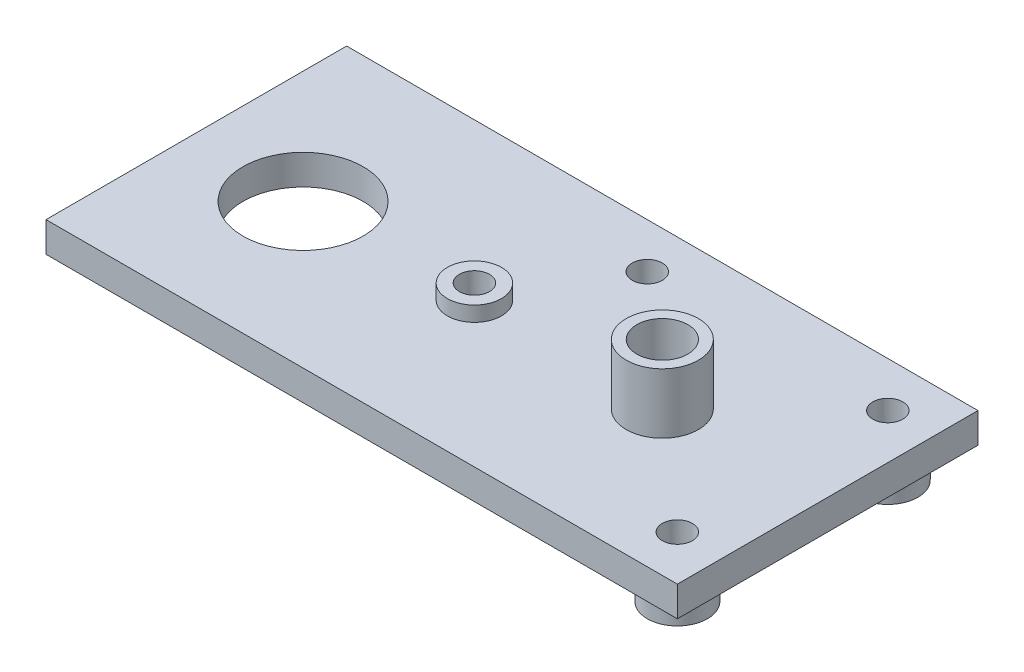
SolidWorks part; units mm, degrees
ref_plane "前视基准面" through (0, 0, 0) normal (0, 0, 1) x (1, 0, 0)
ref_plane "上视基准面" through (0, 0, 0) normal (0, 1, 0) x (1, 0, 0)
ref_plane "右视基准面" through (0, 0, 0) normal (1, 0, 0) x (0, 0, -1)
sketch "草图1" plane through (0, 0, 0) normal (0, 1, 0) x (1, 0, 0)
  line L1 (-10.5, 5) -> (10.5, 5)
  line L2 (-10.5, 5) -> (-10.5, -5)
  line L3 (-10.5, -5) -> (10.5, -5)
  line L4 (10.5, 5) -> (10.5, -5)
  line L5 (-10.5, 5) -> (10.5, -5) construction
  line L6 (-10.5, -5) -> (10.5, 5) construction
  point P0 (0, 0)
  dimension "D1" = 21
  dimension "D2" = 10
extrude "凸台-拉伸1" add sketch "草图1" along normal blind 1
sketch "草图2" plane through (0, 1, 0) normal (0, 1, 0) x (1, 0, 0)
  line L0 (-10.5, -5) -> (10.5, -5) construction
  line L1 (10.5, -5) -> (10.5, 5) construction
  circle A0 centre (5.2, -0.2) radius 1.2
  dimension "D1" = 2.4
  dimension "D2" = 4.8
  dimension "D3" = 5.3
extrude "凸台-拉伸2" add sketch "草图2" along normal blind 2
sketch "草图3" plane through (0, 3, 0) normal (0, 1, 0) x (1, 0, 0)
  circle A0 centre (5.2, -0.2) radius 0.85
  dimension "D1" = 1.7
extrude "切除-拉伸2" cut sketch "草图3" against normal blind 3
sketch "草图5" plane through (0, 1, 0) normal (0, 1, 0) x (1, 0, 0)
  line L0 (-10.5, -5) -> (10.5, -5) construction
  circle A0 centre (-1.05, -0.2) radius 0.9
  circle A1 centre (5.2, -0.2) radius 1.2 construction
  dimension "D2" = 1.8
  dimension "D1" = 4.8
  dimension "D3" = 6.25
extrude "凸台-拉伸3" add sketch "草图5" along normal blind 0.5 and the other way blind 2
sketch "草图7" plane through (0, 1, 0) normal (0, 1, 0) x (1, 0, 0)
  line L0 (-10.5, -5) -> (10.5, -5) construction
  circle A0 centre (-6.75, -0.2) radius 2
  circle A1 centre (-1.05, -0.2) radius 0.9 construction
  dimension "D2" = 4
  dimension "D1" = 5.7
  dimension "D3" = 4.8
extrude "切除-拉伸4" cut sketch "草图7" against normal blind 1
sketch "草图8" plane through (0, 1, 0) normal (0, 1, 0) x (1, 0, 0)
  line L0 (10.5, 5) -> (-10.5, 5) construction
  line L1 (10.5, -5) -> (10.5, 5) construction
  line L2 (-10.5, -5) -> (10.5, -5) construction
  circle A0 centre (9, 3.5) radius 0.5
  circle A1 centre (1, 3.5) radius 0.5
  circle A2 centre (9, -3.5) radius 0.5
  dimension "D1" = 1
  dimension "D2" = 1
  dimension "D3" = 1
  dimension "D4" = 1.5
  dimension "D8" = 1.5
  dimension "D5" = 1.5
  dimension "D6" = 1.5
  dimension "D7" = 8
  dimension "D9" = 1.5
extrude "切除-拉伸5" cut sketch "草图8" against normal blind 1
sketch "草图9" plane through (0, 1.5, 0) normal (0, 1, 0) x (1, 0, 0)
  circle A0 centre (-1.05, -0.2) radius 0.5
  dimension "D1" = 1
extrude "切除-拉伸6" cut sketch "草图9" against normal blind 2
sketch "草图10" plane through (0, 0, 0) normal (0, -1, 0) x (1, 0, 0)
  circle A0 centre (9, 3.5) radius 1
  circle A1 centre (9, -3.5) radius 1
  circle A2 centre (1, -3.5) radius 1
  dimension "D1" = 2
  dimension "D2" = 2
  dimension "D3" = 2
extrude "凸台-拉伸4" add sketch "草图10" along normal blind 1
sketch "草图11" plane through (0, -1, 0) normal (0, -1, 0) x (1, 0, 0)
  circle A0 centre (9, 3.5) radius 0.5
  circle A1 centre (9, -3.5) radius 0.5
  circle A2 centre (1, -3.5) radius 0.5
  dimension "D1" = 1
  dimension "D2" = 1
  dimension "D3" = 1
extrude "切除-拉伸7" cut sketch "草图11" against normal blind 1
